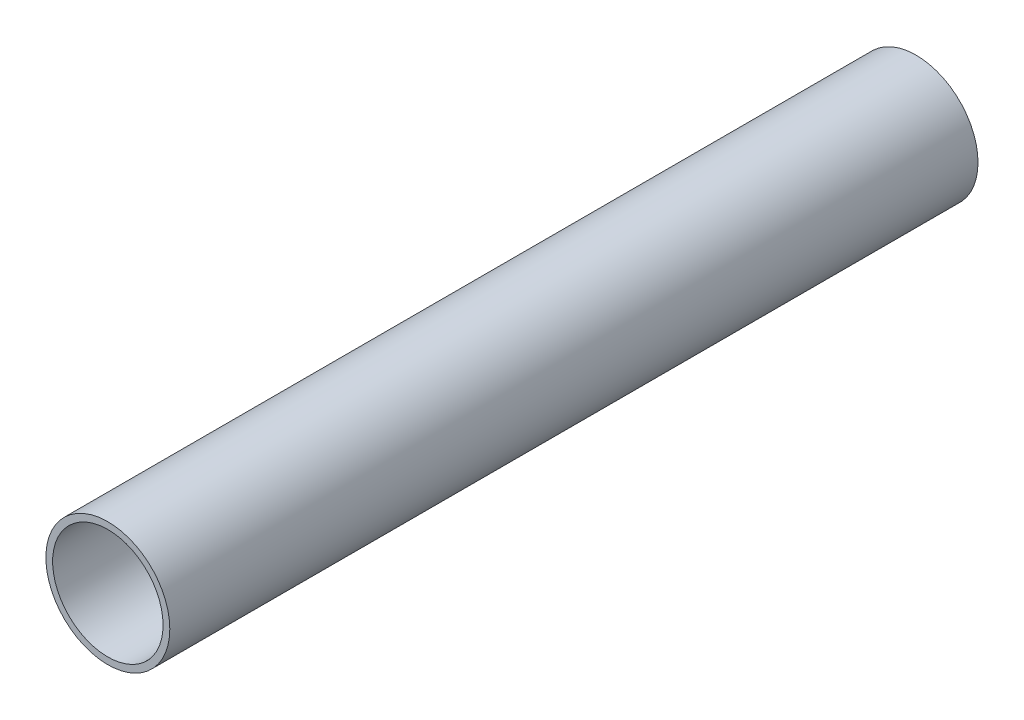
SolidWorks part; units mm, degrees
ref_plane "Alzado" through (0, 0, 0) normal (0, 0, 1) x (1, 0, 0)
ref_plane "Planta" through (0, 0, 0) normal (0, 1, 0) x (1, 0, 0)
ref_plane "Vista lateral" through (0, 0, 0) normal (1, 0, 0) x (0, 0, -1)
sketch "Croquis1" plane through (0, 0, 0) normal (0, 0, 1) x (1, 0, 0)
  circle A0 centre (0, 0) radius 2.05
  circle A1 centre (0, 0) radius 2.3
  dimension "D1" = 4.1
  dimension "D2" = 4.6
extrude "Saliente-Extruir1" add sketch "Croquis1" along normal blind 30 contours A1 A0
equation "\"k\"= 25.884"
equation "\"A_ALETA\"= ( ( ( tan ( \"ANG_ALETA\" ) ) * \"L_ALETA\" ) + \"A_BASE\" )"
equation "\"A_BASE\"= ( \"L_DIE\" - \"E_CAJA\" )"
equation "\"L_ALETA\"=90.000000"
equation "\"TAU_ALETA\"= ( \"L_ALETA\" / ( log ( ( \"A_ALETA\" ) + 1 ) ) )"
equation "\"E_ALETA\"=5.5"
equation "\"R_SONDA\"= 2.05"
equation "\"D_SONDA\"=20.000000"
equation "\"L_CAJA\"=25.000000"
equation "\"E_CAJA\"= 2.5"
equation "\"A_CAJA\"= ( 2 * \"A_BASE\" ) + \"GAP_ALETAS\""
equation "\"W_CAJA\"= \"A_CAJA\" * \"CONST_CAJA\""
equation "\"W_CONC\"= ( \"W_CAJA\" / \"CONST_CONC\" ) "
equation "\"A_CONC\"= ( \"A_CAJA\" / \"CONST_CONC\" )"
equation "\"L_CONC\"= \"D_SONDA\" - \"OFFSET_CONC\""
equation "\"W_ALETA\"=70.000000"
equation "\"L_DIE_SONDA\"= ( \"GAP_ALETAS\" / 4 )"
equation "\"GAP_ALETAS\"=2"
equation "\"D1@Croquis1\" = \"R_SONDA\" * 2"
equation "\"D1@Saliente-Extruir1\" = \"L_DIE\" + \"ALARGUE\""
equation "\"D2@Croquis1\" = 2 * \"R_SONDA\" + \"TOLERANCIA\""
equation "\"CONST_CONC\"=2.000000"
equation "\"K\"= 1.5"
equation "\"L_DIE\"= 15"
equation "\"L_CI\"= 18"
equation "\"CONST_CAJA\"=2.000000"
equation "\"ANG_ALETA\"=15.000000"
equation "\"R_C_SONDA\"= 0.63"
equation "\"TOLERANCIA\"= 0.5"
equation "\"OFFSET_CONC\"= ( 2 * \"R_TORNILLO\" )"
equation "\"R_TORNILLO\"=2.600000"
equation "\"ALARGUE\"=15"
